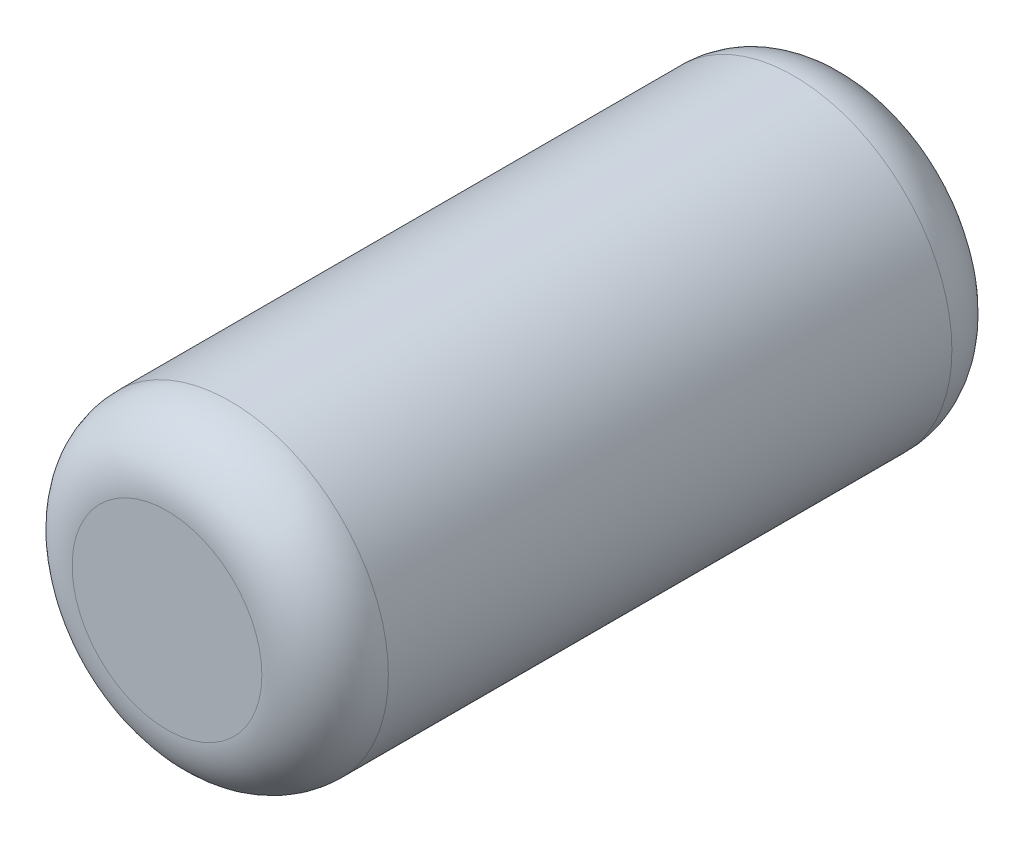
SolidWorks part; units mm, degrees
ref_plane "Front Plane" through (0, 0, 0) normal (0, 0, 1) x (1, 0, 0)
ref_plane "Top Plane" through (0, 0, 0) normal (0, 1, 0) x (1, 0, 0)
ref_plane "Right Plane" through (0, 0, 0) normal (1, 0, 0) x (0, 0, -1)
sketch "Sketch1" plane through (0, 0, 0) normal (0, 0, 1) x (1, 0, 0)
  circle A0 centre (0, 0) radius 34.925
extrude "Boss-Extrude1" add sketch "Sketch1" along normal blind 152.4
fillet "Fillet1" radius 13.97 2 edges at (34.925, 0, 152.4) (34.925, 0, 0)
